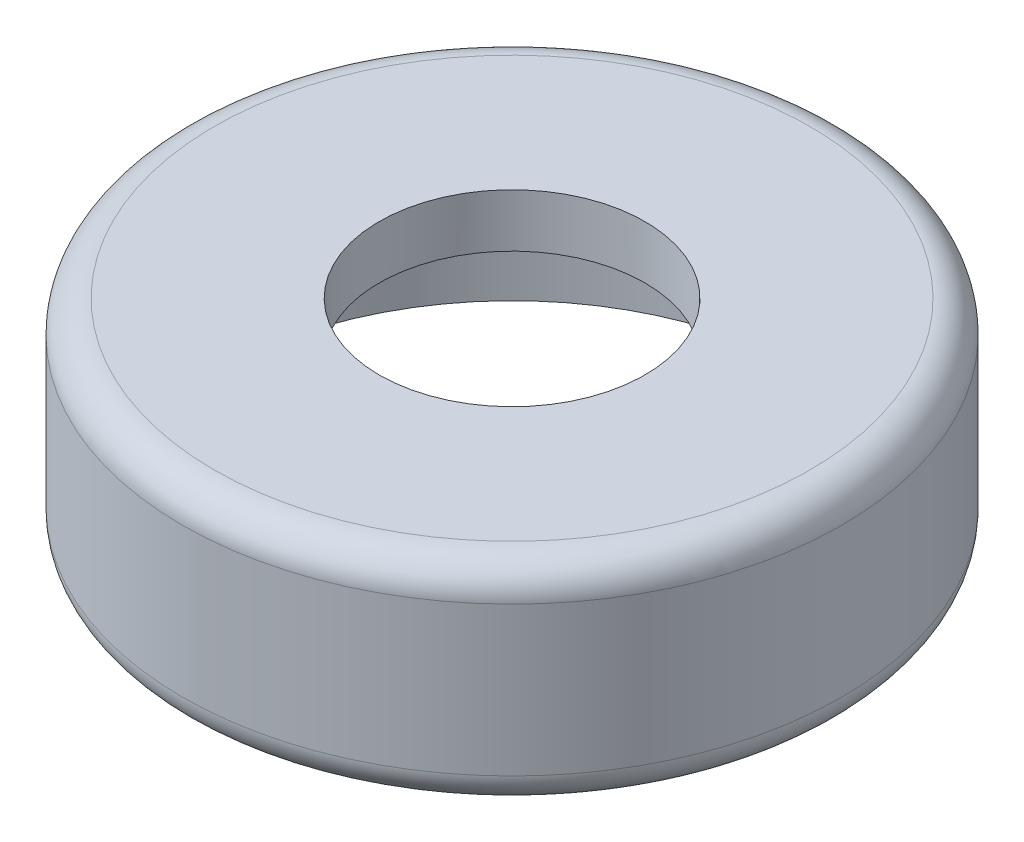
SolidWorks part; units mm, degrees
ref_plane "Front Plane" through (0, 0, 0) normal (0, 0, 1) x (1, 0, 0)
ref_plane "Top Plane" through (0, 0, 0) normal (0, 1, 0) x (1, 0, 0)
ref_plane "Right Plane" through (0, 0, 0) normal (1, 0, 0) x (0, 0, -1)
sketch "Sketch1" plane through (0, 0, 0) normal (0, 1, 0) x (1, 0, 0)
  circle A0 centre (0, 0) radius 31
  dimension "D1" = 62
extrude "Boss-Extrude1" add sketch "Sketch1" along normal blind 20
fillet "Fillet1" radius 3 2 edges at (0, 20, 31) (0, 0, 31)
sketch "Sketch2" plane through (0, 0, 0) normal (0, -1, 0) x (1, 0, 0)
  circle A0 centre (0, 0) radius 28
extrude "Cut-Extrude1" cut sketch "Sketch2" against normal blind 15
sketch "Sketch3" plane through (0, 20, 0) normal (0, 1, 0) x (1, 0, 0)
  circle A0 centre (0, 0) radius 12.5
  dimension "D1" = 25
extrude "Cut-Extrude2" cut sketch "Sketch3" against normal through all both and the other way through all
